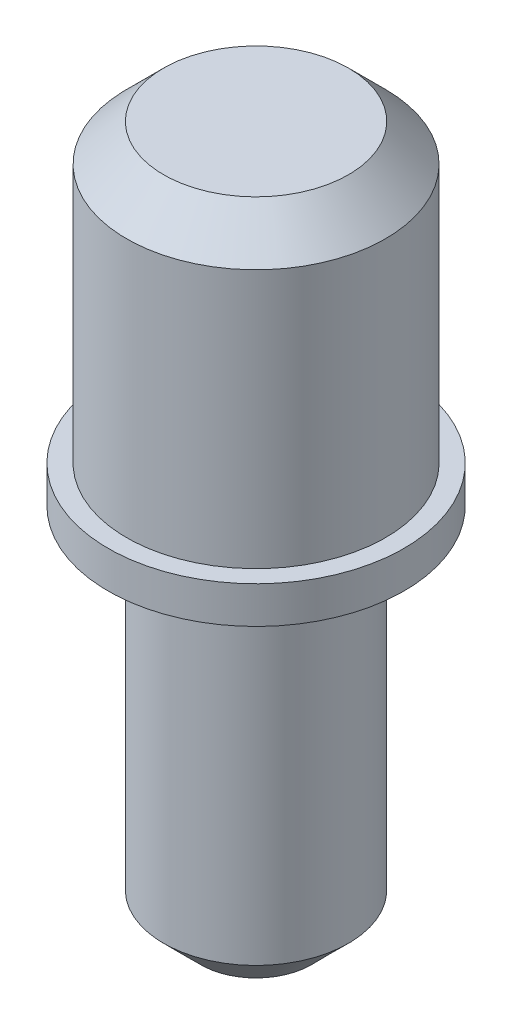
SolidWorks part; units mm, degrees
ref_plane "前视基准面" through (0, 0, 0) normal (0, 0, 1) x (1, 0, 0)
ref_plane "上视基准面" through (0, 0, 0) normal (0, 1, 0) x (1, 0, 0)
ref_plane "右视基准面" through (0, 0, 0) normal (1, 0, 0) x (0, 0, -1)
sketch "草图1" plane through (0, 0, 0) normal (0, 0, 1) x (1, 0, 0)
  line L0 (0, 0) -> (0, 19)
  line L1 (0, 19) -> (2.5, 19)
  line L2 (3.5, 18) -> (3.5, 11)
  line L3 (3.5, 11) -> (4, 11)
  line L4 (4, 11) -> (4, 10)
  line L5 (4, 10) -> (2.5, 10)
  line L6 (2.5, 10) -> (2.5, 1)
  line L7 (1.5, 0) -> (0, 0)
  line L8 (2.5, 19) -> (3.5, 18)
  line L9 (2.5, 1) -> (1.5, 0)
  point P3 (3.5, 19)
  point P9 (2.5, 0)
  dimension "D1" = 3.5
  dimension "D2" = 2.5
  dimension "D3" = 1
  dimension "D4" = 4
  dimension "D5" = 10
  dimension "D6" = 8
revolve "旋转1" add sketch "草图1" angle 360 about L0
